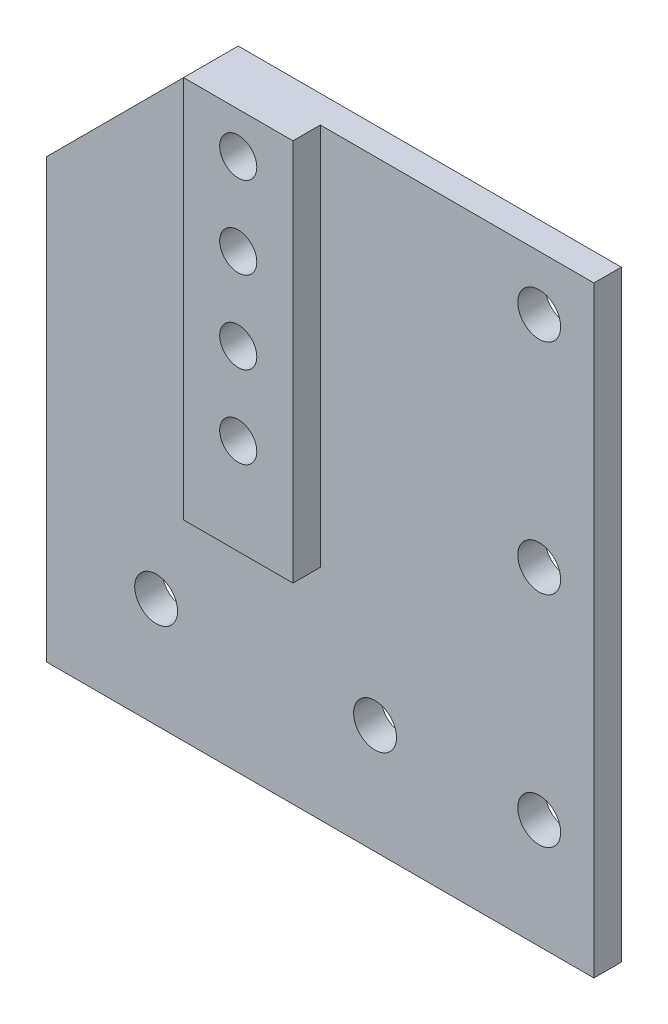
SolidWorks part; units mm, degrees
material "6061 Alloy"
ref_plane "Front Plane" through (0, 0, 0) normal (0, 0, 1) x (1, 0, 0)
ref_plane "Top Plane" through (0, 0, 0) normal (0, 1, 0) x (1, 0, 0)
ref_plane "Right Plane" through (0, 0, 0) normal (1, 0, 0) x (0, 0, -1)
sketch "Sketch1" plane through (0, 0, 0) normal (0, 0, 1) x (1, 0, 0)
  line L15 (-266.7, -12.7) -> (-266.7, 57.15)
  line L16 (-266.7, 609.6) -> (-266.7, -16.7024) construction
  line L18 (-279.4, -12.7) -> (-266.7, -12.7)
  line L19 (-279.4, -12.7) -> (-330.2, -12.7)
  line L20 (-330.2, -12.7) -> (-330.2, 12.7)
  line L21 (-330.2, 12.7) -> (-330.2, 38.1)
  line L22 (-311.15, 57.15) -> (-330.2, 38.1)
  line L23 (-279.4, 57.15) -> (-311.15, 57.15)
  line L24 (-266.7, 57.15) -> (-279.4, 57.15)
  dimension "D1" = 69.85
  dimension "D2" = 50.8
  dimension "D3" = 12.7
extrude "Boss-Extrude1" add sketch "Sketch1" along normal blind 3.175
sketch "Sketch2" plane through (0, 0, 3.175) normal (0, 0, 1) x (1, 0, 0)
  line L0 (-787.4, 12.7) -> (-279.4, 12.7) construction
  line L1 (-787.4, -12.7) -> (-279.4, -12.7) construction
  line L10 (-273.05, 25.4) -> (-273.05, 50.8) construction
  line L11 (-273.05, 0) -> (-273.05, 25.4) construction
  line L12 (-273.05, -12.7) -> (-273.05, 0) construction
  line L13 (-279.4, -12.7) -> (-266.7, -12.7) construction
  line L14 (-330.2, 0) -> (-317.5, 0) construction
  line L15 (-317.5, 0) -> (-292.1, 0) construction
  line L16 (-330.2, -12.7) -> (-330.2, 12.7) construction
  dimension "D1" = 12.7
  dimension "D2" = 25.4
  dimension "D3" = 25.4
  dimension "D4" = 12.7
  dimension "D5" = 25.4
  dimension "D6" = 12.7
  dimension "D7" = 19.05
hole_wizard "#10 Clearance Hole1" positions "Sketch3" profile "Sketch4" hole size "#10" standard "ANSI Inch" end condition through all
sketch "Sketch3" plane through (0, 0, 3.175) normal (0, 0, 1) x (1, 0, 0)
  point P30 (-273.05, 50.8)
  point P33 (-273.05, 25.4)
  point P36 (-273.05, 0)
  point P41 (-317.5, 0)
  point P44 (-292.1, 0)
  point P47 (-273.05, 50.8)
  point P49 (-273.05, 25.4)
  point P51 (-273.05, 0)
  point P53 (-292.1, 0)
  point P55 (-317.5, 0)
sketch "Sketch4" plane through (-273.05, 50.8, 3.175) normal (1, 0, 0) x (0, -1, 0)
  line L0 (0, 0) -> (0, 3.175)
  line L1 (0, 3.175) -> (2.4892, 3.175)
  line L2 (2.4892, 3.175) -> (2.4892, 0)
  line L5 (2.4892, 0) -> (0, 0)
  line L11 (0, -6.35) -> (0, 107.95) construction
  dimension "Thru Hole Dia." = 4.9784
  dimension "Thru Hole Depth" = 3.175
sketch "Sketch5" plane through (0, 0, 3.175) normal (0, 0, 1) x (1, 0, 0)
  line L0 (-311.15, 12.7) -> (-298.45, 12.7)
  line L9 (-311.15, 57.15) -> (-311.15, 12.7)
  line L10 (-298.45, 12.7) -> (-298.45, 57.15)
  line L13 (-266.7, 57.15) -> (-311.15, 57.15) construction
  line L17 (-298.45, 57.15) -> (-311.15, 57.15)
  dimension "D1" = 44.45
  dimension "D2" = 12.7
extrude "Boss-Extrude2" add sketch "Sketch5" along normal blind 3.175
sketch "Sketch6" plane through (0, 0, 6.35) normal (0, 0, 1) x (1, 0, 0)
  line L0 (-304.8, 57.15) -> (-304.8, 52.3875) construction
  line L1 (-304.8, 52.3875) -> (-304.8, 42.8625) construction
  line L2 (-304.8, 42.8625) -> (-304.8, 33.3375) construction
  line L4 (-304.8, 33.3375) -> (-304.8, 23.8125) construction
  line L5 (-298.45, 57.15) -> (-311.15, 57.15) construction
  dimension "D1" = 9.525
  dimension "D2" = 4.7625
  dimension "D3" = 9.525
  dimension "D4" = 9.525
hole_wizard "#8 Clearance Hole1" positions "Sketch7" profile "Sketch8" hole size "#8" standard "ANSI Inch" end condition through all
sketch "Sketch7" plane through (0, 0, 6.35) normal (0, 0, 1) x (1, 0, 0)
  point P0 (-304.8, 42.8625)
  point P3 (-304.8, 52.3875)
  point P7 (-304.8, 33.3375)
  point P10 (-304.8, 23.8125)
sketch "Sketch8" plane through (-304.8, 42.8625, 6.35) normal (1, 0, 0) x (0, -1, 0)
  line L0 (0, 0) -> (0, 6.35)
  line L1 (0, 6.35) -> (2.1526, 6.35)
  line L2 (2.1526, 6.35) -> (2.1526, 0)
  line L5 (2.1526, 0) -> (0, 0)
  line L11 (0, -6.35) -> (0, 107.95) construction
  dimension "Thru Hole Dia." = 4.3053
  dimension "Thru Hole Depth" = 6.35
